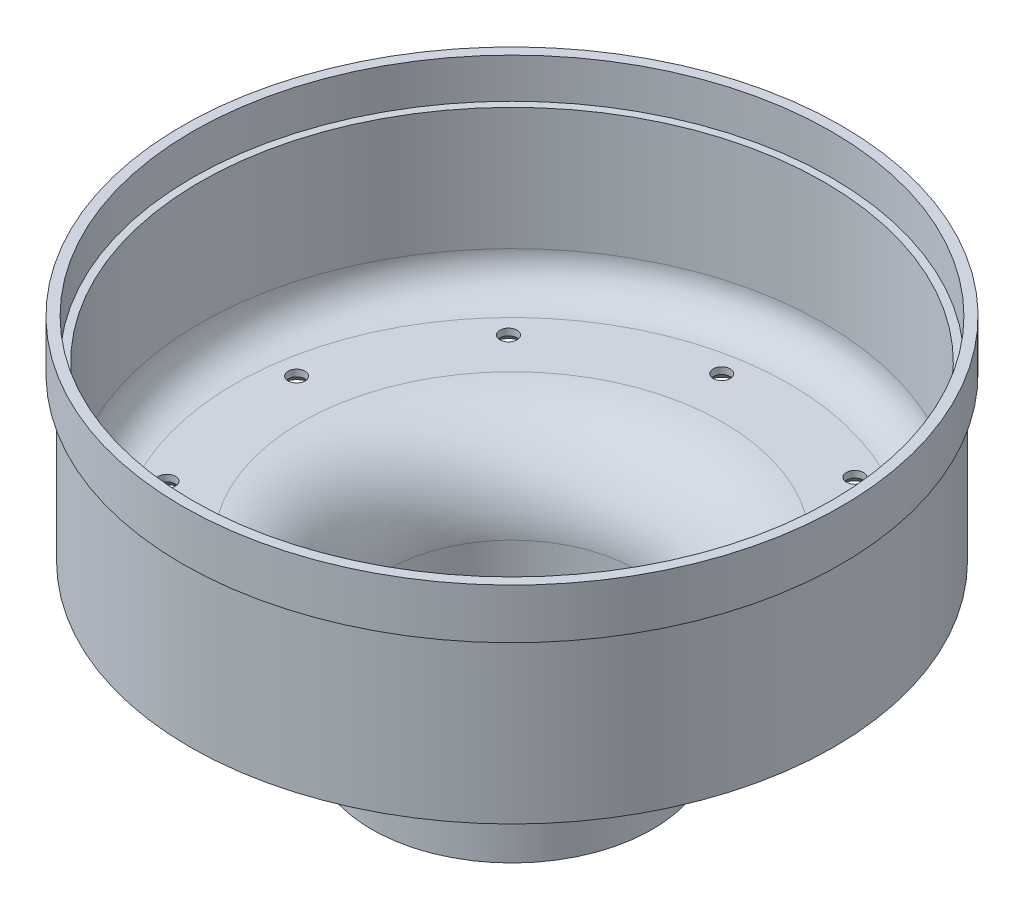
SolidWorks part; units mm, degrees
ref_plane "Ön Düzlem" through (0, 0, 0) normal (0, 0, 1) x (1, 0, 0)
ref_plane "Üst Düzlem" through (0, 0, 0) normal (0, 1, 0) x (1, 0, 0)
ref_plane "Sağ Düzlem" through (0, 0, 0) normal (1, 0, 0) x (0, 0, -1)
sketch "Çizim1" plane through (0, 0, 0) normal (0, 0, 1) x (1, 0, 0)
  line L0 (0, 0) -> (0, 23.9444) construction
  line L1 (26.6, -13.6484) -> (26.6, -3.6484)
  line L2 (26.6, -3.6484) -> (25.1, -3.6484)
  line L3 (25.1, -3.6484) -> (25.1, 4.7516)
  line L4 (42.2, 21.8516) -> (55.5, 21.8516)
  line L5 (62.5, 28.8516) -> (62.5, 53.3516)
  line L6 (62.5, 53.3516) -> (64, 53.3516)
  line L7 (64, 53.3516) -> (64, 61.3516)
  line L8 (26.6, -13.6484) -> (28.1, -13.6484)
  line L9 (28.1, -13.6484) -> (28.1, 6.9716)
  line L10 (39.98, 18.8516) -> (64.5, 18.8516)
  line L11 (64.5, 18.8516) -> (64.5, 51.3516)
  line L12 (64.5, 51.3516) -> (66, 51.3516)
  line L13 (66, 51.3516) -> (66, 61.3516)
  line L14 (66, 61.3516) -> (64, 61.3516)
  arc A0 (28.1, 6.9716) -> (39.98, 18.8516) centre (39.98, 6.9716) cw
  arc A1 (25.1, 4.7516) -> (42.2, 21.8516) centre (42.2, 4.7516) cw
  arc A2 (55.5, 21.8516) -> (62.5, 28.8516) centre (55.5, 28.8516) ccw
  point P21 (25.1, 21.8516)
  dimension "D10" = 11.88
  dimension "D11" = 17.1
  dimension "D15" = 7
  dimension "D1" = 35.5
  dimension "D2" = 25.5
  dimension "D3" = 62.5
  dimension "D4" = 25.1
  dimension "D5" = 1.5
  dimension "D6" = 1.5
  dimension "D7" = 3
  dimension "D8" = 3
  dimension "D9" = 2
  dimension "D12" = 2
  dimension "D13" = 10
  dimension "D14" = 8
  dimension "D16" = 66
  dimension "D17" = 37.4
  dimension "D18" = 32.5
revolve "Döndür2" add sketch "Çizim1" angle 360 about L0
sketch "Çizim2" plane through (0, 18.8516, 0) normal (0, -1, 0) x (1, 0, 0)
  line L0 (0, 0) -> (0, 81.9465) construction
  point P0 (8.5, 50.5)
  dimension "D1" = 8.5
  dimension "D2" = 50.5
hole_wizard "M3 SFHCS İçin Havşa1" positions "3B Çizim1" profile "Çizim3" countersink size "M3" standard "ANSI Metric" end condition through all
sketch3d "3B Çizim1"
  point P0 (8.5, 18.8516, 50.5)
sketch "Çizim3" plane through (8.5, 18.8516, 50.5) normal (1, 0, 0) x (0, 0, -1)
  line L0 (0, 0) -> (0, 42.5)
  line L1 (0, 42.5) -> (1.7, 42.5)
  line L2 (1.7, 42.5) -> (1.7, 1.66)
  line L3 (1.7, 1.66) -> (3.36, 0)
  line L5 (3.36, 0) -> (0, 0)
  line L6 (-1.7, 1.66) -> (-3.36, 0) construction
  line L11 (0, -6.35) -> (0, 107.95) construction
  dimension "Thru Hole Dia." = 3.4
  dimension "Thru Hole Depth" = 42.5
  dimension "Near C'Sink Dia." = 6.72
  dimension "Near C'Sink Angle" = 90
pattern_circular "Dairesel Kaplama1" count 10 over 360 about axis through (0, 0, 0) along (0, 1, 0) of "M3 SFHCS İçin Havşa1"
